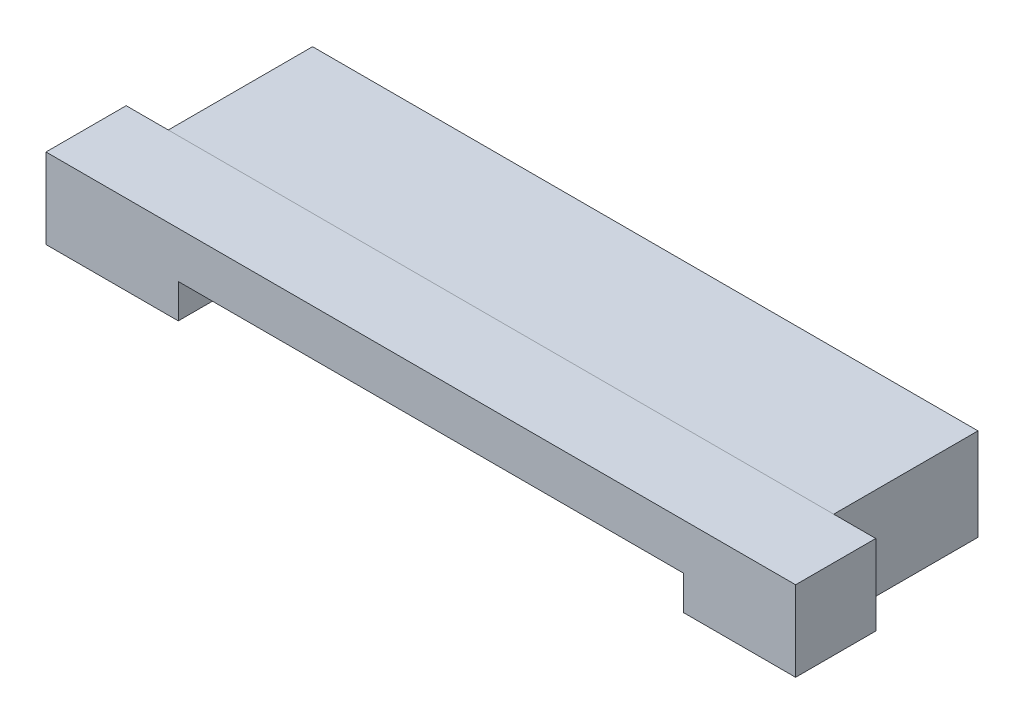
SolidWorks part; units mm, degrees
ref_plane "Front Plane" through (0, 0, 0) normal (0, 0, 1) x (1, 0, 0)
ref_plane "Top Plane" through (0, 0, 0) normal (0, 1, 0) x (1, 0, 0)
ref_plane "Right Plane" through (0, 0, 0) normal (1, 0, 0) x (0, 0, -1)
sketch "Sketch1" plane through (0, 0, 0) normal (0, 1, 0) x (1, 0, 0)
  line L1 (0, 0) -> (16.6, 0)
  line L2 (0, 0) -> (0, 3.6)
  line L3 (0, 3.6) -> (16.6, 3.6)
  line L4 (16.6, 0) -> (16.6, 3.6)
  dimension "D1" = 16.6
  dimension "D2" = 3.6
extrude "Boss-Extrude1" add sketch "Sketch1" along normal blind 2.3
ref_plane "Plane3" through (2.55, 0, 0) normal (-1, 0, 0) x (0, 0, 1)
sketch "Sketch2" plane through (0, 2.3, 0) normal (0, 1, 0) x (1, 0, 0)
  line L0 (0, 3.6) -> (0, 0) construction
  line L1 (17.65, 0) -> (-1.05, 0)
  line L2 (17.65, 0) -> (17.65, -2)
  line L3 (17.65, -2) -> (-1.05, -2)
  line L4 (-1.05, 0) -> (-1.05, -2)
  dimension "D1" = 18.7
  dimension "D2" = 2
  dimension "D3" = 1.05
extrude "Boss-Extrude2" add sketch "Sketch2" against normal blind 2 separate body
sketch "Sketch3" plane through (2.55, 0, 0) normal (-1, 0, 0) x (0, 0, 1)
  line L0 (-3.6, 0) -> (-4.6, 0)
  line L5 (-4.6, 0) -> (-4.6, 0.3)
  line L6 (-4.6, 0.3) -> (-3.9, 0.3)
  line L7 (-3.9, 0.3) -> (-3.9, 0.7)
  line L8 (-3.9, 0.7) -> (-3.6, 0.7)
  line L9 (-3.6, 0.7) -> (-3.6, 0)
  line L10 (-3.6, 2.3) -> (-3.6, 0) construction
  dimension "D1" = 1
  dimension "D2" = 0.7
  dimension "D3" = 0.7
  dimension "D4" = 0.3
  dimension "D5" = 0
extrude "Boss-Extrude5" add sketch "Sketch3" along normal blind 0.1 and the other way blind 0.1
pattern_linear "LPattern2" count 24 spacing 0.5 along (1, 0, 0) of "Boss-Extrude5"
sketch "Sketch4" plane through (0, 0, 2) normal (0, 0, 1) x (1, 0, 0)
  line L0 (-1.05, 0.3) -> (17.65, 0.3) construction
  line L1 (14.85, 1.1524) -> (2.25, 1.1524)
  line L2 (14.85, 1.1524) -> (14.85, 0.3)
  line L3 (14.85, 0.3) -> (2.25, 0.3)
  line L4 (2.25, 1.1524) -> (2.25, 0.3)
  line L5 (17.65, 0.3) -> (17.65, 2.3) construction
  dimension "D1" = 12.6
  dimension "D2" = 0
  dimension "D3" = 2.8
extrude "Cut-Extrude2" cut sketch "Sketch4" against normal blind 2
